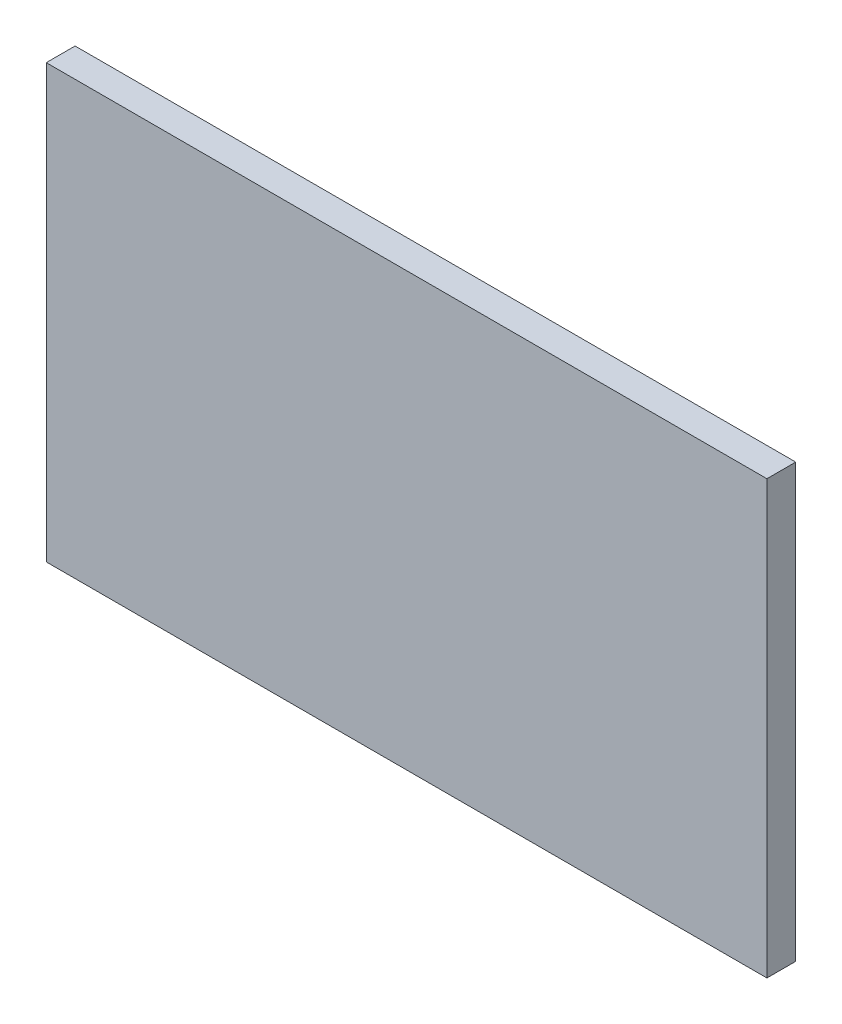
SolidWorks part; units mm, degrees
ref_plane "Front" through (0, 0, 0) normal (0, 0, 1) x (1, 0, 0)
ref_plane "Top" through (0, 0, 0) normal (0, 1, 0) x (1, 0, 0)
ref_plane "Right" through (0, 0, 0) normal (1, 0, 0) x (0, 0, -1)
sketch "Sketch1" plane through (0, 0, 0) normal (0, 0, 1) x (1, 0, 0)
  line L1 (-12.5, 7.5) -> (12.5, 7.5)
  line L2 (-12.5, 7.5) -> (-12.5, -7.5)
  line L3 (-12.5, -7.5) -> (12.5, -7.5)
  line L4 (12.5, 7.5) -> (12.5, -7.5)
  line L5 (-12.5, 7.5) -> (12.5, -7.5) construction
  line L6 (-12.5, -7.5) -> (12.5, 7.5) construction
  point P0 (0, 0)
  dimension "D1" = 25
  dimension "D2" = 15
extrude "Boss-Extrude1" add sketch "Sketch1" along normal blind 1
